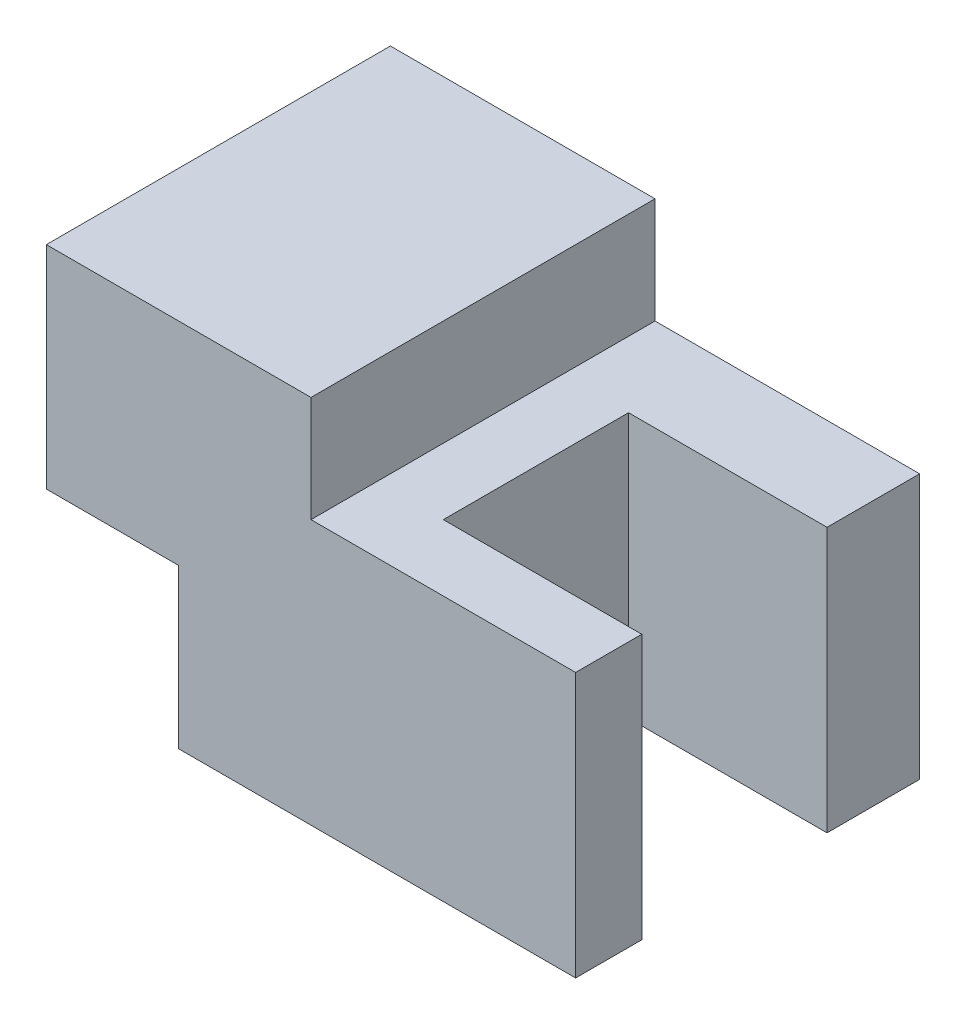
SolidWorks part; units mm, degrees
ref_plane "Ön Düzlem" through (0, 0, 0) normal (0, 0, 1) x (1, 0, 0)
ref_plane "Üst Düzlem" through (0, 0, 0) normal (0, 1, 0) x (1, 0, 0)
ref_plane "Sağ Düzlem" through (0, 0, 0) normal (1, 0, 0) x (0, 0, -1)
sketch "Çizim1" plane through (0, 0, 0) normal (0, 0, 1) x (1, 0, 0)
  line L1 (-508, 1422.4) -> (508, 1422.4)
  line L2 (-508, 1422.4) -> (-508, 609.6)
  line L3 (-508, 609.6) -> (0, 609.6)
  line L4 (508, 1422.4) -> (508, 1016)
  line L5 (508, 1016) -> (1524, 1016)
  line L6 (0, 609.6) -> (0, 0)
  line L7 (0, 0) -> (1524, 0)
  line L8 (1524, 1016) -> (1524, 0)
  dimension "D1" = 1016
  dimension "D2" = 812.8
  dimension "D3" = 609.6
  dimension "D4" = 1524
  dimension "D5" = 1016
  dimension "D6" = 1016
extrude "Yükseklik-Ekstrüzyon1" add sketch "Çizim1" along normal blind 1320.8
sketch "Çizim2" plane through (0, 1016, 0) normal (0, 1, 0) x (1, 0, 0)
  line L0 (1524, -1320.8) -> (1524, 0) construction
  line L1 (762, -355.6) -> (1524, -355.6)
  line L2 (762, -355.6) -> (762, -1066.8)
  line L3 (762, -1066.8) -> (1524, -1066.8)
  line L4 (1524, -355.6) -> (1524, -1066.8)
  line L5 (1524, -1320.8) -> (508, -1320.8) construction
  line L6 (1524, 0) -> (508, 0) construction
  dimension "D1" = 254
  dimension "D2" = 355.6
  dimension "D3" = 762
extrude "Kes-Ekstrüzyon2" cut sketch "Çizim2" against normal blind 1016 contours L2 L1 L4 L3
